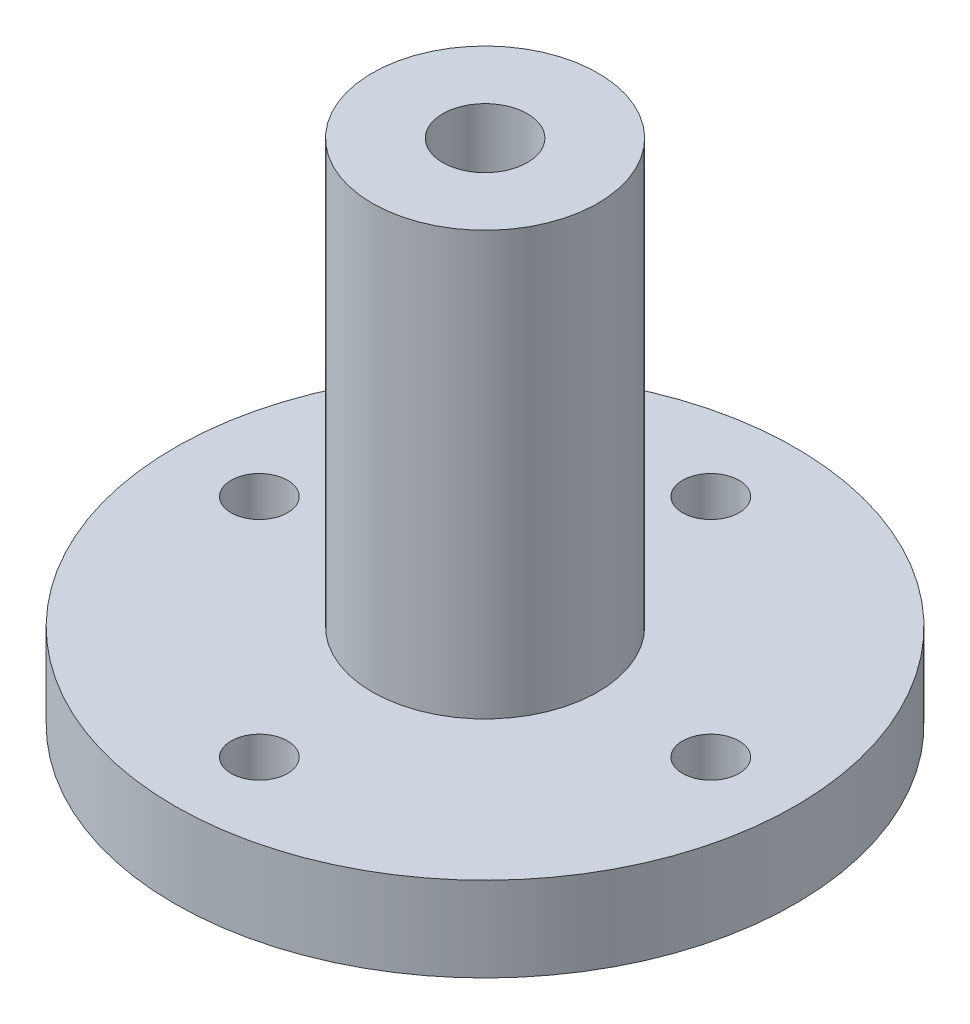
SolidWorks part; units mm, degrees
ref_plane "Front Plane" through (0, 0, 0) normal (0, 0, 1) x (1, 0, 0)
ref_plane "Top Plane" through (0, 0, 0) normal (0, 1, 0) x (1, 0, 0)
ref_plane "Right Plane" through (0, 0, 0) normal (1, 0, 0) x (0, 0, -1)
sketch "Sketch1" plane through (0, 0, 0) normal (0, 1, 0) x (1, 0, 0)
  line L0 (0, 0) -> (0, 8) construction
  circle A0 centre (0, 0) radius 11
  circle A1 centre (0, 8) radius 1
  circle A2 centre (8, 0) radius 1
  circle A3 centre (0, -8) radius 1
  circle A4 centre (-8, 0) radius 1
  dimension "D1" = 22
  dimension "D2" = 2
  dimension "D5" = 8
  dimension "D4" = 4
extrude "Boss-Extrude1" add sketch "Sketch1" along normal blind 3
sketch "Sketch2" plane through (0, 3, 0) normal (0, 1, 0) x (1, 0, 0)
  circle A1 centre (0, 0) radius 4
  dimension "D1" = 8
extrude "Boss-Extrude2" add sketch "Sketch2" along normal blind 15
sketch "Sketch3" plane through (0, 18, 0) normal (0, 1, 0) x (1, 0, 0)
  circle A0 centre (0, 0) radius 1.5
  dimension "D1" = 3
extrude "Cut-Extrude1" cut sketch "Sketch3" against normal blind 5
